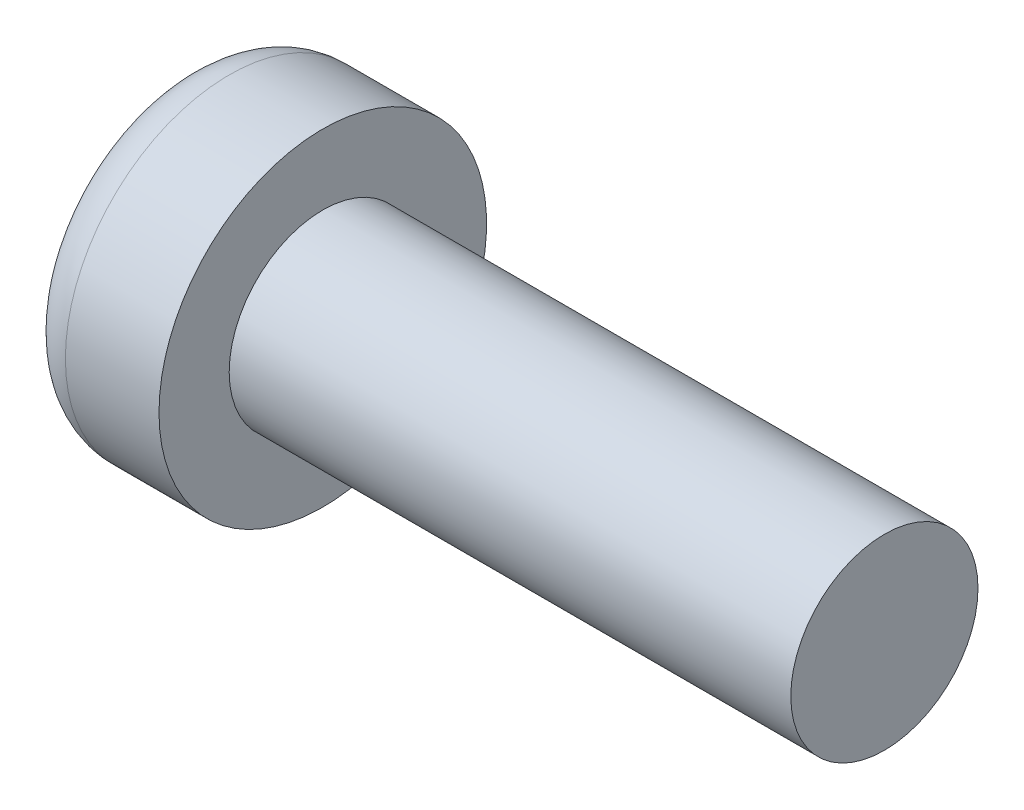
SolidWorks part; units mm, degrees
ref_plane "Front Plane" through (0, 0, 0) normal (0, 0, 1) x (1, 0, 0)
ref_plane "Top Plane" through (0, 0, 0) normal (0, 1, 0) x (1, 0, 0)
ref_plane "Right Plane" through (0, 0, 0) normal (1, 0, 0) x (0, 0, -1)
sketch "Sketch1" plane through (0, 0, 0) normal (0, 0, 1) x (1, 0, 0)
  line L0 (0, 0) -> (7.5, 0) construction
  line L2 (0, 0) -> (0.9852, 0)
  line L3 (0, 0) -> (0, 1.25)
  line L4 (0.5, 1.75) -> (1.5, 1.75)
  line L5 (1.5, 1) -> (1.5, 1.75)
  line L6 (1.5, 1) -> (7.5, 1)
  line L8 (0.9852, 0) -> (7.5, 0)
  line L9 (7.5, 1) -> (7.5, 0)
  arc A0 (0, 1.25) -> (0.5, 1.75) centre (0.5, 1.25) cw
  point P10 (0, 1.75)
  dimension "D5" = 0.5
  dimension "D1" = 1.75
  dimension "D2" = 1.5
  dimension "D3" = 6
  dimension "D4" = 1
revolve "Revolve1" add sketch "Sketch1" angle 360 about L0
